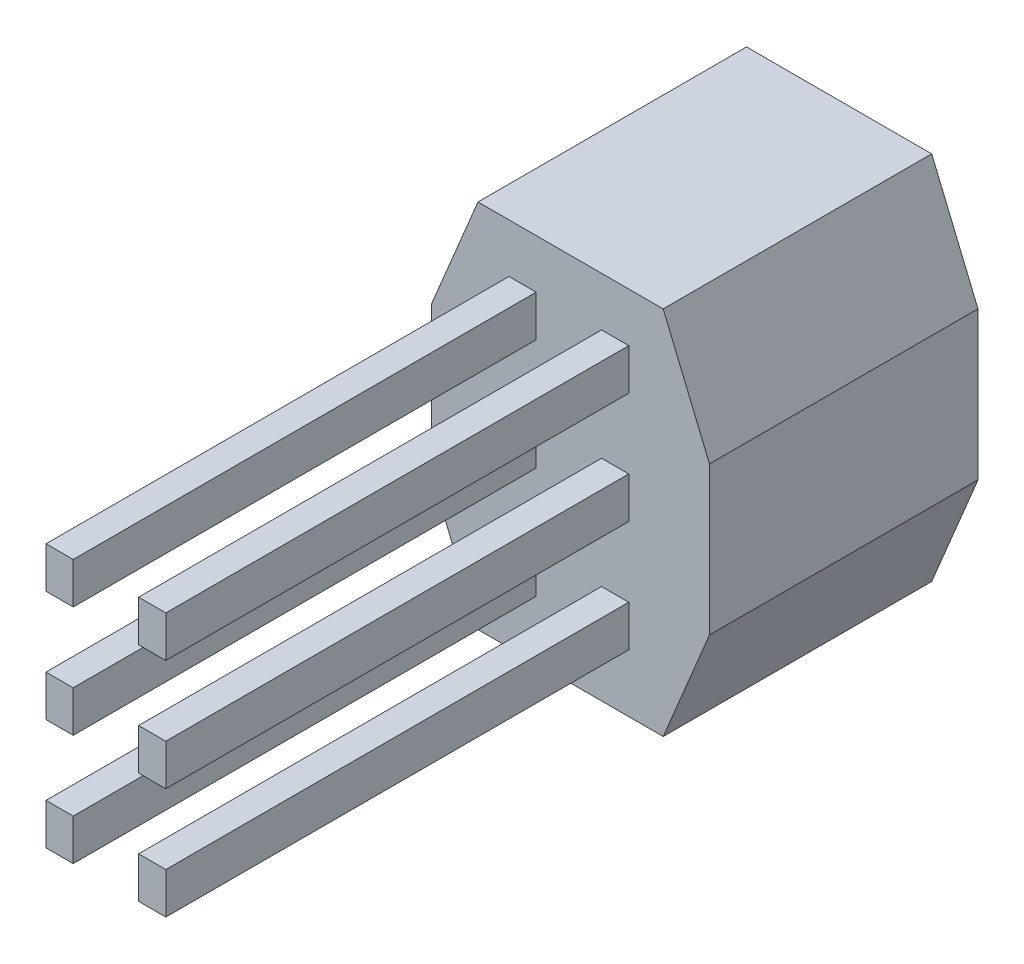
SolidWorks part; units mm, degrees
ref_plane "Спереди" through (0, 0, 0) normal (0, 0, 1) x (1, 0, 0)
ref_plane "Сверху" through (0, 0, 0) normal (0, 1, 0) x (1, 0, 0)
ref_plane "Справа" through (0, 0, 0) normal (1, 0, 0) x (0, 0, -1)
sketch "Эскиз1" plane through (0, 0, 0) normal (0, 0, 1) x (1, 0, 0)
  line L0 (-392.8148, 89.7206) -> (-392.3148, 90.9206)
  line L1 (-392.3148, 90.9206) -> (-390.3148, 90.9206)
  line L2 (-392.8148, 89.7206) -> (-392.8148, 88.1206)
  line L3 (-392.3148, 86.9206) -> (-390.3148, 86.9206)
  line L5 (-392.8148, 88.1206) -> (-392.3148, 86.9206)
  line L6 (-389.8148, 89.7206) -> (-390.3148, 90.9206)
  line L7 (-389.8148, 88.1206) -> (-390.3148, 86.9206)
  line L8 (-389.8148, 89.7206) -> (-389.8148, 88.1206)
  point P0 (-392.8148, 90.9206)
  point P2 (-392.8148, 86.9206)
  dimension "D1" = 4
  dimension "D2" = 2
  dimension "D3" = 0.5
  dimension "D4" = 1.2
  dimension "D5" = 1.2
  dimension "D6" = 0.5
extrude "Бобышка-Вытянуть1" add sketch "Эскиз1" along normal blind 2.9
sketch "Эскиз2" plane through (0, 0, 2.9) normal (0, 0, 1) x (1, 0, 0)
  line L0 (-390.9804, 90.3908) -> (-390.9804, 89.9462)
  line L1 (-391.9804, 90.3908) -> (-391.6865, 90.3908)
  line L2 (-391.9804, 90.3908) -> (-391.9804, 89.9462)
  line L3 (-391.9804, 89.9462) -> (-391.6865, 89.9462)
  line L4 (-391.6865, 90.3908) -> (-391.6865, 89.9462)
  line L5 (-390.9804, 90.3908) -> (-390.6865, 90.3908)
  line L6 (-390.6865, 90.3908) -> (-390.6865, 89.9462)
  line L7 (-390.9804, 89.9462) -> (-390.6865, 89.9462)
  line L8 (-390.9804, 89.1908) -> (-390.9804, 88.7462)
  line L9 (-390.9804, 89.1908) -> (-390.6865, 89.1908)
  line L10 (-390.6865, 89.1908) -> (-390.6865, 88.7462)
  line L11 (-390.9804, 88.7462) -> (-390.6865, 88.7462)
  line L12 (-390.9804, 87.9908) -> (-390.9804, 87.5462)
  line L13 (-390.9804, 87.9908) -> (-390.6865, 87.9908)
  line L14 (-390.6865, 87.9908) -> (-390.6865, 87.5462)
  line L15 (-390.9804, 87.5462) -> (-390.6865, 87.5462)
  line L16 (-391.9804, 89.1908) -> (-391.9804, 88.7462)
  line L17 (-391.9804, 89.1908) -> (-391.6865, 89.1908)
  line L18 (-391.6865, 89.1908) -> (-391.6865, 88.7462)
  line L19 (-391.9804, 88.7462) -> (-391.6865, 88.7462)
  line L20 (-391.9804, 87.9908) -> (-391.9804, 87.5462)
  line L21 (-391.9804, 87.9908) -> (-391.6865, 87.9908)
  line L22 (-391.6865, 87.9908) -> (-391.6865, 87.5462)
  line L23 (-391.9804, 87.5462) -> (-391.6865, 87.5462)
  dimension "D1" = 2
  dimension "D2" = 3
extrude "Бобышка-Вытянуть2" add sketch "Эскиз2" along normal blind 5 contours L2 L1 L4 L3
ref_plane "Плоскость2" through (0, 88.9206, 0) normal (0, -1, 0) x (-1, 0, 0)
ref_plane "Плоскость3" through (0, 0, 1.45) normal (0, 0, 1) x (1, 0, 0)
